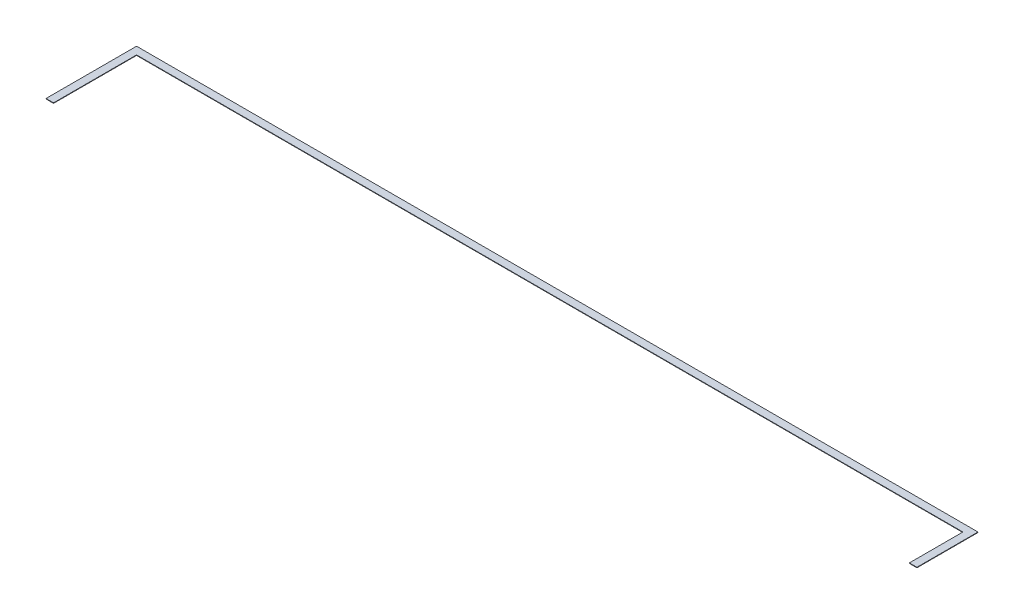
SolidWorks part; units mm, degrees
ref_plane "Front Plane" through (0, 0, 0) normal (0, 0, 1) x (1, 0, 0)
ref_plane "Top Plane" through (0, 0, 0) normal (0, 1, 0) x (1, 0, 0)
ref_plane "Right Plane" through (0, 0, 0) normal (1, 0, 0) x (0, 0, -1)
sketch "Sketch1" plane through (0, 0, 0) normal (0, 1, 0) x (1, 0, 0)
  line L0 (0, 609.6) -> (5664.2, 609.6)
  line L1 (0, 0) -> (50.8, 0)
  line L2 (0, 0) -> (0, 609.6)
  line L4 (50.8, 0) -> (50.8, 558.8)
  line L5 (0, 0) -> (50.8, 0) construction
  line L6 (5664.2, 609.6) -> (5664.2, 198.4375)
  line L7 (5664.2, 198.4375) -> (5613.4, 198.4375)
  line L8 (5613.4, 198.4375) -> (5613.4, 558.8)
  line L9 (5613.4, 558.8) -> (50.8, 558.8)
  line L10 (50.8, 558.8) -> (50.8, 609.6) construction
  dimension "D1" = 50.8
  dimension "D2" = 609.6
  dimension "D3" = 5664.2
  dimension "D4" = 411.1625
extrude "Boss-Extrude1" add sketch "Sketch1" along normal blind 3.175
